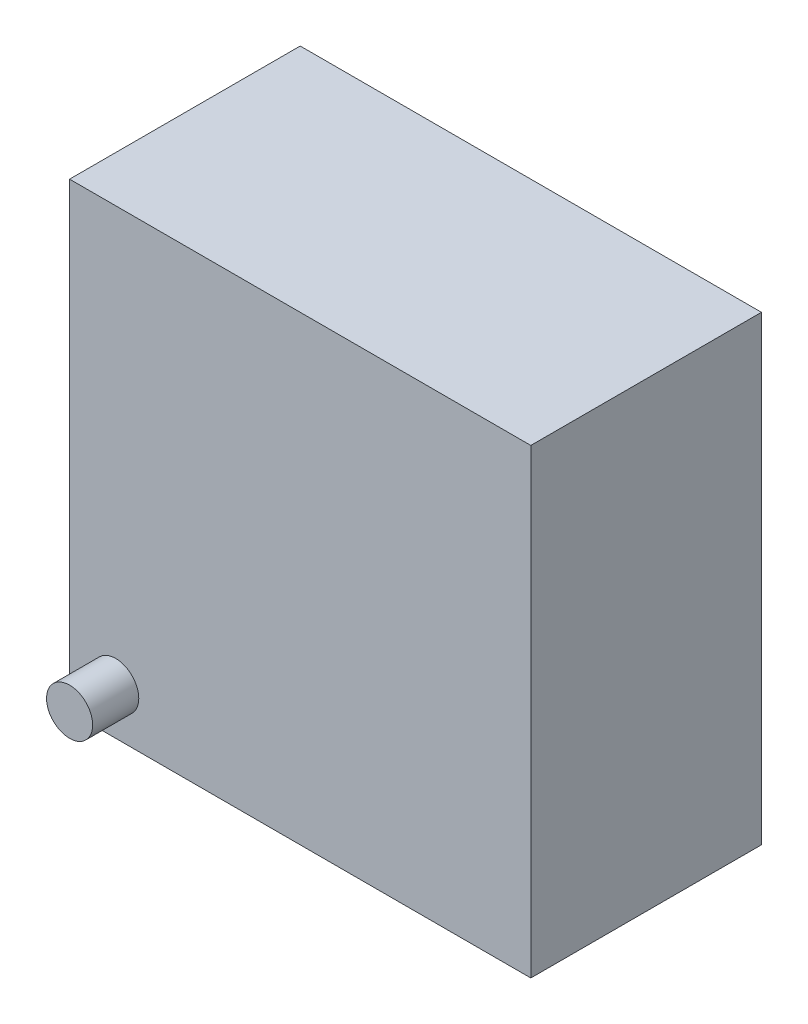
SolidWorks part; units mm, degrees
ref_plane "前视基准面" through (0, 0, 0) normal (0, 0, 1) x (1, 0, 0)
ref_plane "上视基准面" through (0, 0, 0) normal (0, 1, 0) x (1, 0, 0)
ref_plane "右视基准面" through (0, 0, 0) normal (1, 0, 0) x (0, 0, -1)
other "Configuration Table"
sketch "草图1" plane through (0, 0, 0) normal (0, 0, 1) x (1, 0, 0)
  line L1 (0, 0) -> (20, 0)
  line L2 (0, 0) -> (0, 20)
  line L3 (0, 20) -> (20, 20)
  line L4 (20, 0) -> (20, 20)
extrude "BaseBox" add sketch "草图1" along normal blind 10
sketch "草图2" plane through (0, 0, 10) normal (0, 0, 1) x (1, 0, 0)
  circle A0 centre (2, 2) radius 1
extrude "BossSeed" add sketch "草图2" along normal blind 2
pattern_linear "LinearPattern" count 2 spacing 20 along (-1, 0, 0) count 3 spacing 25 along (0, 1, 0) of "BossSeed"
